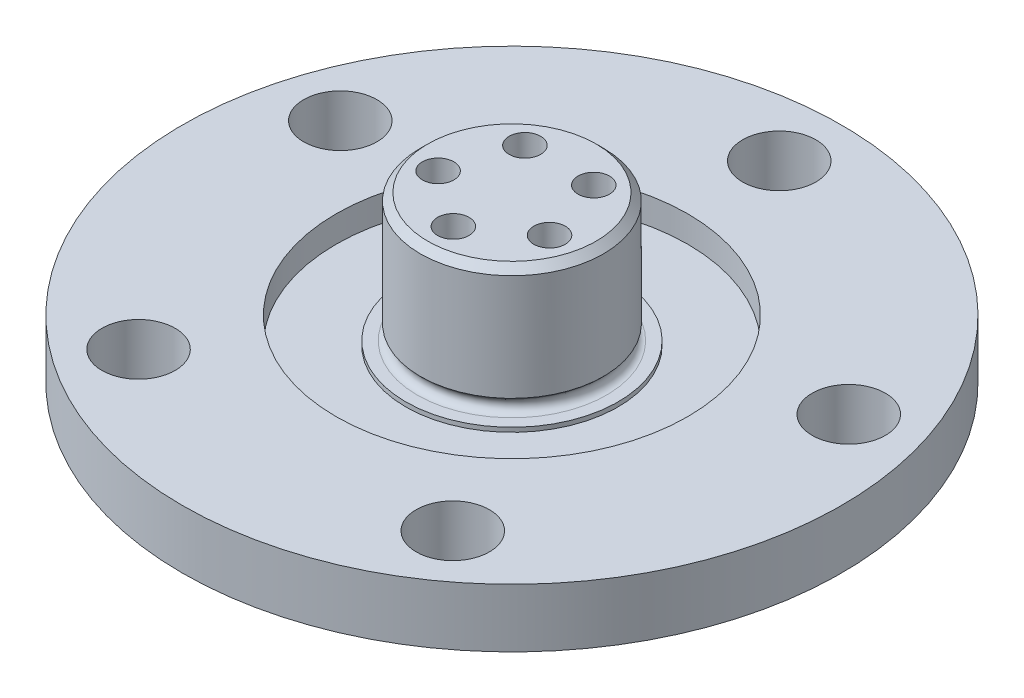
SolidWorks part; units mm, degrees
ref_plane "Front Plane" through (0, 0, 0) normal (0, 0, 1) x (1, 0, 0)
ref_plane "Top Plane" through (0, 0, 0) normal (0, 1, 0) x (1, 0, 0)
ref_plane "Right Plane" through (0, 0, 0) normal (1, 0, 0) x (0, 0, -1)
sketch "Sketch1" plane through (0, 0, 0) normal (0, 1, 0) x (1, 0, 0)
  circle A0 centre (0, 0) radius 36.5 construction
  circle A1 centre (0, 36.5) radius 5
  circle A2 centre (34.7136, 11.2791) radius 5
  circle A3 centre (21.4542, -29.5291) radius 5
  circle A4 centre (-21.4542, -29.5291) radius 5
  circle A5 centre (-34.7136, 11.2791) radius 5
  circle A6 centre (0, 0) radius 45
  point P16 (0, 0)
  dimension "D1" = 73
  dimension "D2" = 10
  dimension "D4" = 90
  dimension "D3" = 5
extrude "Boss-Extrude1" add sketch "Sketch1" along normal blind 8
hole_wizard "Ø4.3 (4.3) Diameter Hole1" positions "Sketch4" profile "Sketch5" hole size "Ø4.3" standard "DIN" end condition through all
sketch "Sketch4" plane through (0, 8, 0) normal (0, 1, 0) x (1, 0, 0)
  line L0 (-34.7136, 11.2791) -> (0, 0) construction
  line L1 (0, 0) -> (0, 36.5) construction
  line L3 (0, 0) -> (-21.4542, 29.5291) construction
  line L5 (0, 36.5) -> (-21.4542, 29.5291) construction
  line L7 (-34.7136, 11.2791) -> (-21.4542, 29.5291) construction
  circle A0 centre (0, 0) radius 8 construction
  point P21 (-4.7023, 6.4721)
  point P27 (4.7023, 6.4721)
  point P28 (7.6085, -2.4721)
  point P29 (0, -8)
  point P30 (-7.6085, -2.4721)
  dimension "D1" = 16
  dimension "D2" = 5
sketch "Sketch5" plane through (-7.6085, 8, 2.4721) normal (1, 0, 0) x (0, 0, 1)
  line L0 (0, 0) -> (0, 8)
  line L1 (0, 8) -> (2.15, 8)
  line L2 (2.15, 8) -> (2.15, 0)
  line L5 (2.15, 0) -> (0, 0)
  line L11 (0, -6.35) -> (0, 107.95) construction
  dimension "Thru Hole Dia." = 4.3
  dimension "Thru Hole Depth" = 8
sketch "Sketch6" plane through (0, 0, 0) normal (0, -1, 0) x (1, 0, 0)
  circle A0 centre (0, 0) radius 19.9
  circle A1 centre (0, 0) radius 30.1
  dimension "D1" = 39.8
  dimension "D2" = 60.2
extrude "Cut-Extrude2" cut sketch "Sketch6" against normal blind 1.5
sketch "Sketch8" plane through (0, 8, 0) normal (0, 1, 0) x (1, 0, 0)
  circle A0 centre (0, 0) radius 12.5
  circle A1 centre (0, 0) radius 24
  dimension "D1" = 25
  dimension "D2" = 48
extrude "Cut-Extrude3" cut sketch "Sketch8" against normal blind 3
sketch "Sketch9" plane through (0, 5, 0) normal (0, 1, 0) x (1, 0, 0)
  circle A0 centre (0, 0) radius 24 construction
  circle A1 centre (0, 0) radius 24 construction
  circle A5 centre (0, 0) radius 14.5
  circle A6 centre (0, 0) radius 24 construction
  circle A7 centre (0, 0) radius 24
extrude "Cut-Extrude4" cut sketch "Sketch9" against normal blind 0.6
sketch "Sketch10" plane through (0, 8, 0) normal (0, -1, 0) x (1, 0, 0)
  circle A0 centre (7.6085, 2.4721) radius 2.15 construction
  circle A3 centre (4.7023, -6.4721) radius 2.15 construction
  circle A4 centre (-4.7023, -6.4721) radius 2.15 construction
  circle A5 centre (-7.6085, 2.4721) radius 2.15 construction
  circle A6 centre (0, 8) radius 2.15 construction
  circle A7 centre (7.6085, 2.4721) radius 2.15
  circle A8 centre (4.7023, -6.4721) radius 2.15
  circle A9 centre (-4.7023, -6.4721) radius 2.15
  circle A10 centre (-7.6085, 2.4721) radius 2.15
  circle A11 centre (0, 8) radius 2.15
  circle A12 centre (0, 0) radius 12.5
  circle A13 centre (0, 0) radius 12.5
  dimension "D1" = 0
extrude "Boss-Extrude2" add sketch "Sketch10" against normal blind 14.5
chamfer "Chamfer1" distance 1 angle 45 1 edges at (0, 22.5, -12.5)
sketch "Sketch11" plane through (0, 0, 0) normal (0, 0, 1) x (1, 0, 0)
  line L5 (12.5, 5) -> (12.5, 7)
  line L6 (12.5, 5) -> (-12.5, 5) construction
  line L7 (14.5, 5) -> (-14.5, 5) construction
  line L8 (12.5, 7) -> (10.5, 5)
  line L9 (10.5, 5) -> (12.5, 5)
  dimension "D2" = 2
ref_axis "Axis1" through (0, 1.5, 0) along (0, -1, 0)
revolve "Cut-Revolve1" cut sketch "Sketch11" angle 360 about axis through (0, 1.5, 0) along (0, -1, 0)
fillet "Fillet1" radius 1 1 edges at (0, 5, 10.5)
